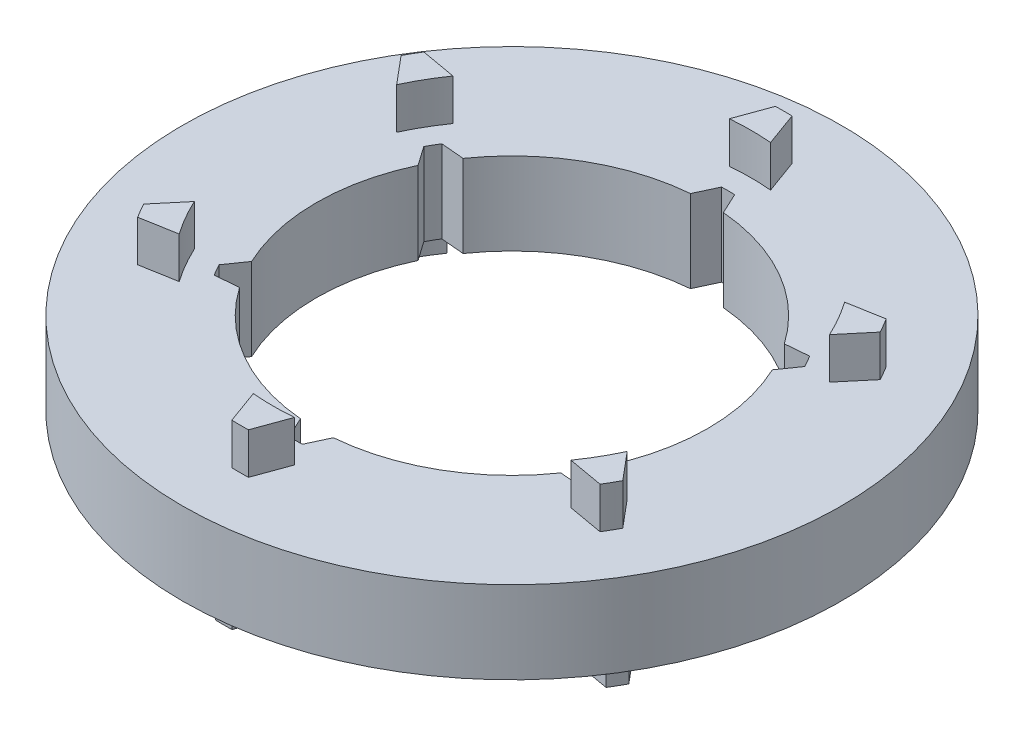
SolidWorks part; units mm, degrees
ref_plane "Front Plane" through (0, 0, 0) normal (0, 0, 1) x (1, 0, 0)
ref_plane "Top Plane" through (0, 0, 0) normal (0, 1, 0) x (1, 0, 0)
ref_plane "Right Plane" through (0, 0, 0) normal (1, 0, 0) x (0, 0, -1)
sketch "Sketch1" plane through (0, 0, 0) normal (0, 1, 0) x (1, 0, 0)
  line L0 (0, 0) -> (0, 34.5685) construction
  line L1 (-2, 26.1737) -> (-2, 23.6656) construction
  line L2 (-2, 23.6656) -> (-0.8006, 26.2378)
  line L3 (2, 23.6656) -> (0.8006, 26.2378)
  line L4 (19.495, 13.5649) -> (22.3223, 13.8122)
  line L5 (21.495, 10.1008) -> (23.1229, 12.4256)
  line L6 (21.495, -10.1008) -> (23.1229, -12.4256)
  line L7 (19.495, -13.5649) -> (22.3223, -13.8122)
  line L8 (2, -23.6656) -> (0.8006, -26.2378)
  line L9 (-2, -23.6656) -> (-0.8006, -26.2378)
  line L10 (-19.495, -13.5649) -> (-22.3223, -13.8122)
  line L11 (-21.495, -10.1008) -> (-23.1229, -12.4256)
  line L12 (-21.495, 10.1008) -> (-23.1229, 12.4256)
  line L13 (-19.495, 13.5649) -> (-22.3223, 13.8122)
  arc A0 (-2, 23.6656) -> (-19.495, 13.5649) centre (0, 0) ccw
  arc A1 (0.8006, 26.2378) -> (-0.8006, 26.2378) centre (0, 0) ccw
  arc A2 (23.1229, 12.4256) -> (22.3223, 13.8122) centre (0, 0) ccw
  arc A3 (22.3223, -13.8122) -> (23.1229, -12.4256) centre (0, 0) ccw
  arc A4 (-0.8006, -26.2378) -> (0.8006, -26.2378) centre (0, 0) ccw
  arc A5 (-23.1229, -12.4256) -> (-22.3223, -13.8122) centre (0, 0) ccw
  arc A6 (-22.3223, 13.8122) -> (-23.1229, 12.4256) centre (0, 0) ccw
  arc A7 (-21.495, 10.1008) -> (-21.495, -10.1008) centre (0, 0) ccw
  arc A8 (19.495, 13.5649) -> (2, 23.6656) centre (0, 0) ccw
  arc A9 (21.495, -10.1008) -> (21.495, 10.1008) centre (0, 0) ccw
  arc A10 (2, -23.6656) -> (19.495, -13.5649) centre (0, 0) ccw
  arc A11 (-19.495, -13.5649) -> (-2, -23.6656) centre (0, 0) ccw
  circle A12 centre (0, 0) radius 40
  point P30 (0, 0)
  dimension "D1" = 47.5
  dimension "D2" = 52.5
  dimension "D6" = 80
  dimension "D3" = 2
  dimension "D4" = 25
  dimension "D5" = 6
extrude "Boss-Extrude1" add sketch "Sketch1" along normal blind 10
sketch "4,5,6" plane through (0, 10, 0) normal (0, 1, 0) x (1, 0, 0)
  line L0 (0, 23.5241) -> (0, 36.2824) construction
  line L1 (2.5, 35.9681) -> (2.5, 28.892) construction
  line L2 (2.5, 28.892) -> (1.0105, 32.9845)
  line L3 (-2.5, 28.892) -> (-1.0105, 32.9845)
  line L4 (23.7712, 16.6111) -> (28.0602, 17.3673)
  line L5 (26.2712, 12.281) -> (29.0707, 15.6172)
  line L6 (26.2712, -12.281) -> (29.0707, -15.6172)
  line L7 (23.7712, -16.6111) -> (28.0602, -17.3673)
  line L8 (2.5, -28.892) -> (1.0105, -32.9845)
  line L9 (-2.5, -28.892) -> (-1.0105, -32.9845)
  line L10 (-23.7712, -16.6111) -> (-28.0602, -17.3673)
  line L11 (-26.2712, -12.281) -> (-29.0707, -15.6172)
  line L12 (-26.2712, 12.281) -> (-29.0707, 15.6172)
  line L13 (-23.7712, 16.6111) -> (-28.0602, 17.3673)
  arc A0 (2.5, 28.892) -> (-2.5, 28.892) centre (0, 0) ccw
  arc A1 (1.0105, 32.9845) -> (-1.0105, 32.9845) centre (0, 0) ccw
  arc A2 (26.2712, 12.281) -> (23.7712, 16.6111) centre (0, 0) ccw
  arc A3 (29.0707, 15.6172) -> (28.0602, 17.3673) centre (0, 0) ccw
  arc A4 (23.7712, -16.6111) -> (26.2712, -12.281) centre (0, 0) ccw
  arc A5 (28.0602, -17.3673) -> (29.0707, -15.6172) centre (0, 0) ccw
  arc A6 (-2.5, -28.892) -> (2.5, -28.892) centre (0, 0) ccw
  arc A7 (-1.0105, -32.9845) -> (1.0105, -32.9845) centre (0, 0) ccw
  arc A8 (-26.2712, -12.281) -> (-23.7712, -16.6111) centre (0, 0) ccw
  arc A9 (-29.0707, -15.6172) -> (-28.0602, -17.3673) centre (0, 0) ccw
  arc A10 (-23.7712, 16.6111) -> (-26.2712, 12.281) centre (0, 0) ccw
  arc A11 (-28.0602, 17.3673) -> (-29.0707, 15.6172) centre (0, 0) ccw
  point P31 (0, 0)
  dimension "D1" = 58
  dimension "D2" = 66
  dimension "D3" = 2.5
  dimension "D4" = 20
  dimension "D5" = 6
sketch "1,2,3" plane through (0, 10, 0) normal (0, 1, 0) x (1, 0, 0)
  line L0 (0, 18.8714) -> (0, 44.4172) construction
  line L1 (2.5, 34.9106) -> (2.5, 30.899) construction
  line L2 (2.5, 30.899) -> (1.0127, 34.9853)
  line L3 (-2.5, 30.899) -> (-1.0127, 34.9853)
  line L4 (25.5093, 17.6146) -> (29.7918, 18.3697)
  line L5 (28.0093, 13.2845) -> (30.8045, 16.6156)
  line L6 (28.0093, -13.2845) -> (30.8045, -16.6156)
  line L7 (25.5093, -17.6146) -> (29.7918, -18.3697)
  line L8 (2.5, -30.899) -> (1.0127, -34.9853)
  line L9 (-2.5, -30.899) -> (-1.0127, -34.9853)
  line L10 (-25.5093, -17.6146) -> (-29.7918, -18.3697)
  line L11 (-28.0093, -13.2845) -> (-30.8045, -16.6156)
  line L12 (-28.0093, 13.2845) -> (-30.8045, 16.6156)
  line L13 (-25.5093, 17.6146) -> (-29.7918, 18.3697)
  arc A0 (2.5, 30.899) -> (-2.5, 30.899) centre (0, 0) ccw
  arc A1 (1.0127, 34.9853) -> (-1.0127, 34.9853) centre (0, 0) ccw
  arc A2 (28.0093, 13.2845) -> (25.5093, 17.6146) centre (0, 0) ccw
  arc A3 (30.8045, 16.6156) -> (29.7918, 18.3697) centre (0, 0) ccw
  arc A4 (25.5093, -17.6146) -> (28.0093, -13.2845) centre (0, 0) ccw
  arc A5 (29.7918, -18.3697) -> (30.8045, -16.6156) centre (0, 0) ccw
  arc A6 (-2.5, -30.899) -> (2.5, -30.899) centre (0, 0) ccw
  arc A7 (-1.0127, -34.9853) -> (1.0127, -34.9853) centre (0, 0) ccw
  arc A8 (-28.0093, -13.2845) -> (-25.5093, -17.6146) centre (0, 0) ccw
  arc A9 (-30.8045, -16.6156) -> (-29.7918, -18.3697) centre (0, 0) ccw
  arc A10 (-25.5093, 17.6146) -> (-28.0093, 13.2845) centre (0, 0) ccw
  arc A11 (-29.7918, 18.3697) -> (-30.8045, 16.6156) centre (0, 0) ccw
  point P32 (0, 0)
  dimension "D1" = 62
  dimension "D2" = 70
  dimension "D3" = 2.5
  dimension "D4" = 20
  dimension "D5" = 6
extrude "Boss-Extrude2" add sketch "4,5,6" along normal blind 5
extrude "Boss-Extrude4" add sketch "1,2,3" against normal blind 5 from surface at -10 starting at face at (0, 0, 40)
